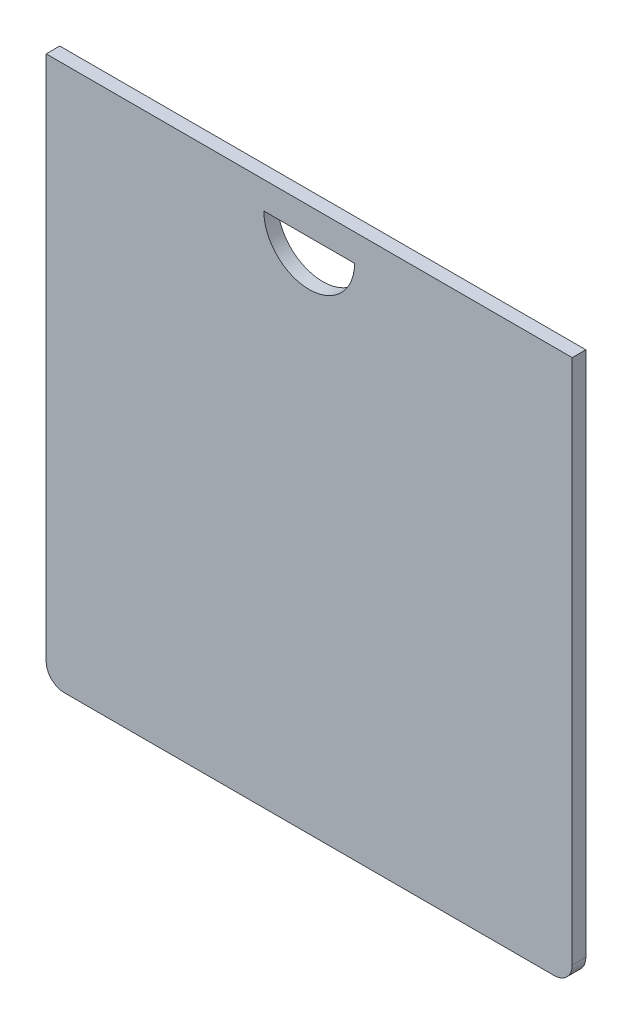
SolidWorks part; units mm, degrees
material "ABS"
ref_plane "Спереди" through (0, 0, 0) normal (0, 0, 1) x (1, 0, 0)
ref_plane "Сверху" through (0, 0, 0) normal (0, 1, 0) x (1, 0, 0)
ref_plane "Справа" through (0, 0, 0) normal (1, 0, 0) x (0, 0, -1)
sketch "Эскиз1" plane through (0, 0, 0) normal (0, 0, 1) x (1, 0, 0)
  line L1 (0, 60) -> (58, 60)
  line L2 (0, 60) -> (0, 0)
  line L3 (0, 0) -> (58, 0)
  line L4 (58, 60) -> (58, 0)
  dimension "D1" = 60
  dimension "D2" = 58
extrude "Бобышка-Вытянуть1" add sketch "Эскиз1" along normal blind 1.5
fillet "Скругление1" radius 2 2 edges at (58, 0, 0.75) (0, 0, 0.75)
sketch "Эскиз2" plane through (0, 0, 1.5) normal (0, 0, 1) x (1, 0, 0)
  line L0 (24, 57) -> (34, 57)
  line L1 (58, 60) -> (0, 60) construction
  arc A0 (24, 57) -> (34, 57) centre (29, 57) ccw
  point P7 (29, 60)
  dimension "D2" = 5
  dimension "D1" = 3
extrude "Вырез-Вытянуть1" cut sketch "Эскиз2" against normal through all
